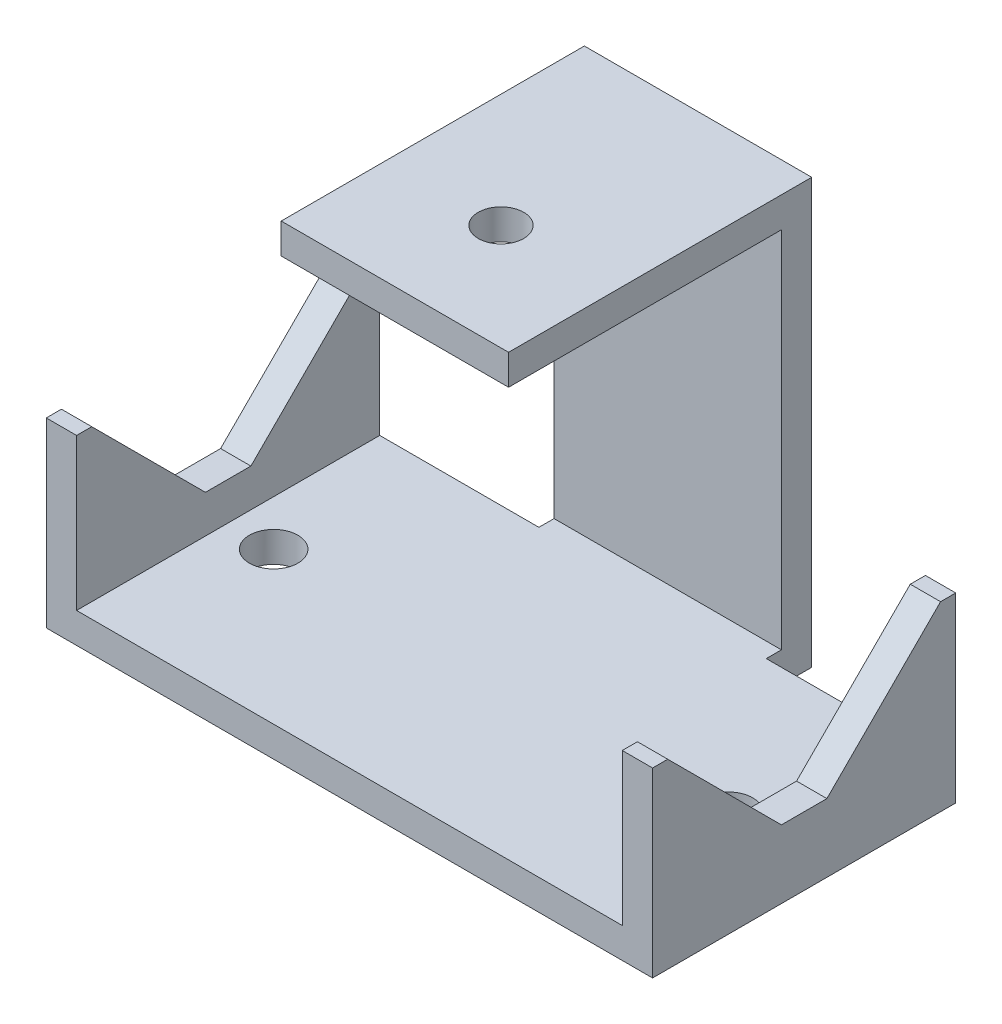
SolidWorks part; units mm, degrees
ref_plane "前视基准面" through (0, 0, 0) normal (0, 0, 1) x (1, 0, 0)
ref_plane "上视基准面" through (0, 0, 0) normal (0, 1, 0) x (1, 0, 0)
ref_plane "右视基准面" through (0, 0, 0) normal (1, 0, 0) x (0, 0, -1)
sketch "草图1" plane through (0, 0, 0) normal (0, 1, 0) x (1, 0, 0)
  line L0 (7.5, 10) -> (20, 10)
  line L1 (-20, -10) -> (20, -10)
  line L2 (-20, -10) -> (-20, 10)
  line L3 (-20, 10) -> (-7.5, 10)
  line L4 (20, -10) -> (20, 10)
  line L5 (-20, -10) -> (20, 10) construction
  line L6 (-20, 10) -> (20, -10) construction
  line L7 (-7.5, 13) -> (7.5, 13)
  line L8 (-7.5, 13) -> (-7.5, 10)
  line L10 (7.5, 13) -> (7.5, 10)
  line L11 (-7.5, 13) -> (7.5, 10) construction
  line L12 (-7.5, 10) -> (7.5, 13) construction
  point P0 (0, 0)
  point P6 (0, 11.5)
  dimension "D1" = 40
  dimension "D2" = 20
  dimension "D3" = 15
  dimension "D4" = 3
extrude "凸台-拉伸1" add sketch "草图1" along normal blind 2
sketch "草图2" plane through (0, 0, -13) normal (0, 0, -1) x (-1, 0, 0)
  line L0 (-20, 0) -> (-7.5, 0) construction
  line L1 (-7.5, 0) -> (7.5, 0)
  line L2 (-7.5, 0) -> (-7.5, 28)
  line L3 (-7.5, 28) -> (7.5, 28)
  line L4 (7.5, 0) -> (7.5, 28)
  line L5 (-7.5, 2) -> (-7.5, 0) construction
  dimension "D1" = 28
extrude "凸台-拉伸2" add sketch "草图2" against normal blind 2
sketch "草图3" plane through (-20, 0, 0) normal (-1, 0, 0) x (0, 0, 1)
  line L0 (1.5, 4.5) -> (9, 12)
  line L1 (-10, 0) -> (10, 0)
  line L2 (-10, 0) -> (-10, 12)
  line L3 (-10, 12) -> (-9, 12)
  line L4 (10, 0) -> (10, 12)
  line L6 (0, -1000) -> (0, 49000) construction
  line L7 (-9, 12) -> (-1.5, 4.5)
  line L9 (9, 12) -> (10, 12)
  line L10 (-1.5, 4.5) -> (1.5, 4.5)
  dimension "D1" = 12
  dimension "D2" = 1
  dimension "D3" = 3
  dimension "D4" = 45
extrude "凸台-拉伸3" add sketch "草图3" against normal blind 2
mirror "镜向1" about plane through (0, 0, 0) normal (1, 0, 0) of "凸台-拉伸3"
sketch "草图4" plane through (0, 28, 0) normal (0, 1, 0) x (1, 0, 0)
  line L1 (-7.5, 13) -> (7.5, 13)
  line L2 (-7.5, 13) -> (-7.5, -7)
  line L3 (-7.5, -7) -> (7.5, -7)
  line L4 (7.5, 13) -> (7.5, -7)
  dimension "D1" = 20
extrude "凸台-拉伸4" add sketch "草图4" against normal blind 2
sketch "草图5" plane through (0, 2, 0) normal (0, 1, 0) x (1, 0, 0)
  line L0 (-1000, 0) -> (49000, 0) construction
  line L1 (0, -1000) -> (0, 49000) construction
  circle A0 centre (-15, 0) radius 1.6
  circle A1 centre (15, 0) radius 1.6
  dimension "D1" = 3.2
  dimension "D2" = 30
extrude "切除-拉伸1" cut sketch "草图5" against normal up to next
sketch "草图6" plane through (0, 28, 0) normal (0, 1, 0) x (1, 0, 0)
  circle A0 centre (0, 0) radius 1.5
  dimension "D1" = 3
extrude "切除-拉伸2" cut sketch "草图6" against normal up to next
